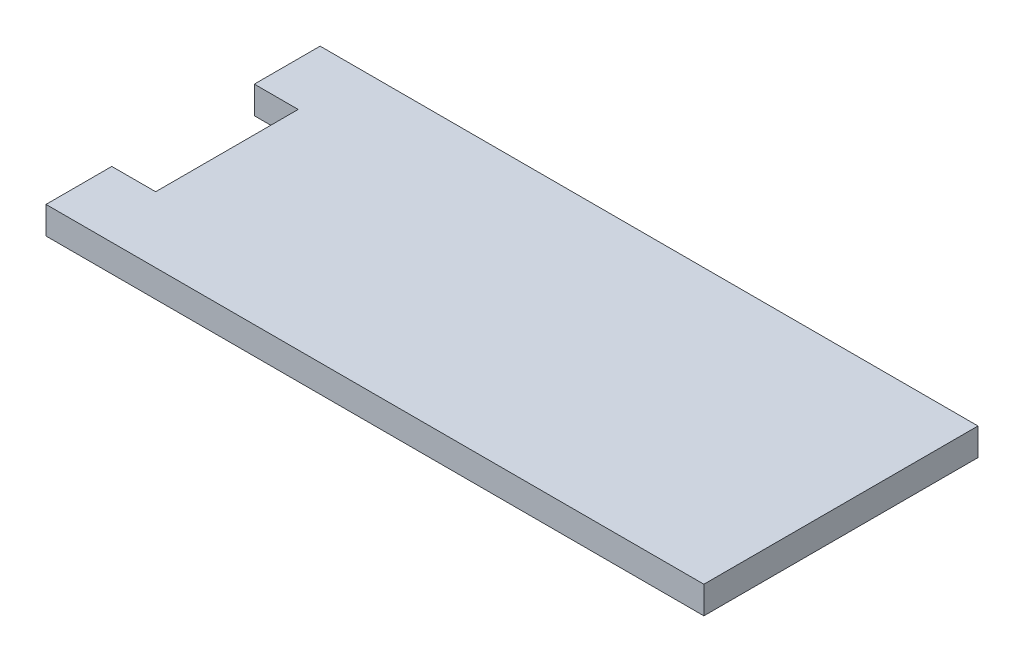
SolidWorks part; units mm, degrees
ref_plane "Front Plane" through (0, 0, 0) normal (0, 0, 1) x (1, 0, 0)
ref_plane "Top Plane" through (0, 0, 0) normal (0, 1, 0) x (1, 0, 0)
ref_plane "Right Plane" through (0, 0, 0) normal (1, 0, 0) x (0, 0, -1)
sketch "Sketch1" plane through (0, 0, 0) normal (0, 1, 0) x (1, 0, 0)
  line L1 (-38.1, 15.875) -> (38.1, 15.875)
  line L2 (-38.1, 15.875) -> (-38.1, -15.875)
  line L3 (-38.1, -15.875) -> (38.1, -15.875)
  line L4 (38.1, 15.875) -> (38.1, -15.875)
  line L5 (-38.1, 15.875) -> (38.1, -15.875) construction
  line L6 (-38.1, -15.875) -> (38.1, 15.875) construction
  point P0 (0, 0)
  dimension "D1" = 31.75
  dimension "D2" = 76.2
extrude "Boss-Extrude1" add sketch "Sketch1" along normal blind 3.175
sketch "Sketch2" plane through (0, 3.175, 0) normal (0, 1, 0) x (1, 0, 0)
  line L0 (-38.1, 15.875) -> (-38.1, -15.875) construction
  line L1 (-38.1, 8.255) -> (-33.02, 8.255)
  line L2 (-38.1, 8.255) -> (-38.1, -8.255)
  line L3 (-38.1, -8.255) -> (-33.02, -8.255)
  line L4 (-33.02, 8.255) -> (-33.02, -8.255)
  line L5 (38.1, 15.875) -> (-38.1, 15.875) construction
  line L6 (-38.1, -15.875) -> (38.1, -15.875) construction
  dimension "D1" = 7.62
  dimension "D2" = 7.62
  dimension "D3" = 5.08
extrude "Cut-Extrude1" cut sketch "Sketch2" against normal blind 3.175
